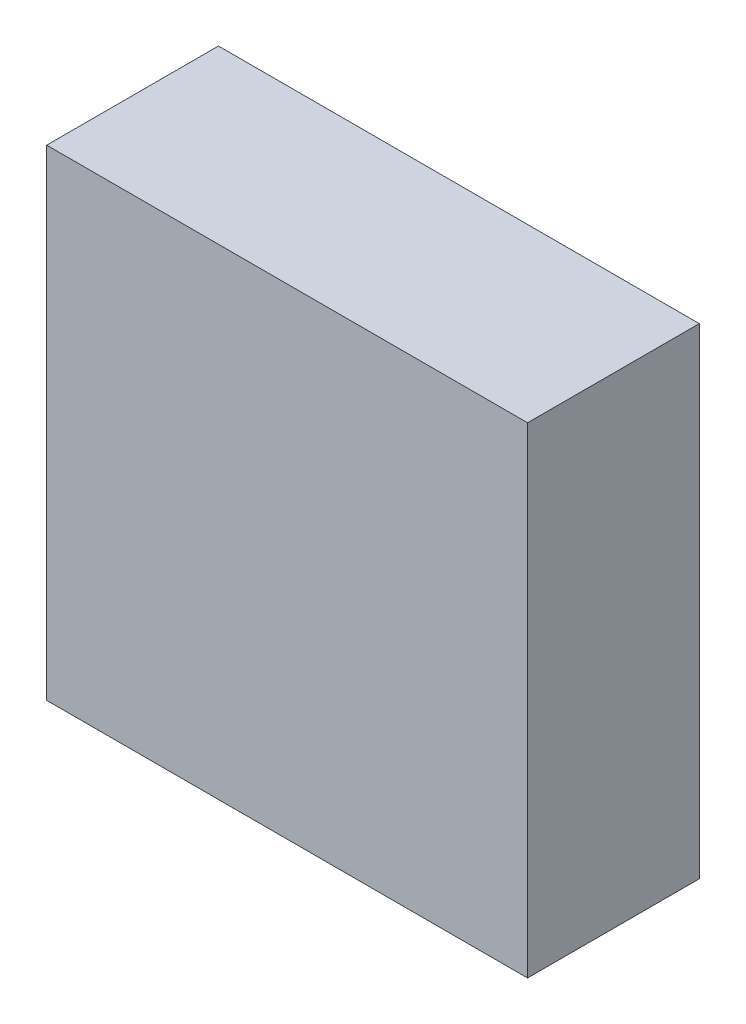
SolidWorks part; units mm, degrees
ref_plane "Front Plane" through (0, 0, 0) normal (0, 0, 1) x (1, 0, 0)
ref_plane "Top Plane" through (0, 0, 0) normal (0, 1, 0) x (1, 0, 0)
ref_plane "Right Plane" through (0, 0, 0) normal (1, 0, 0) x (0, 0, -1)
sketch "Sketch1" plane through (0, 0, 0) normal (0, 0, 1) x (1, 0, 0)
  line L1 (-14, 14) -> (14, 14)
  line L2 (-14, 14) -> (-14, -14)
  line L3 (-14, -14) -> (14, -14)
  line L4 (14, 14) -> (14, -14)
  line L5 (-14, 14) -> (14, -14) construction
  line L6 (-14, -14) -> (14, 14) construction
  point P0 (0, 0)
extrude "Boss-Extrude1" add sketch "Sketch1" against normal blind 10 contours L2 L1 L4 L3
